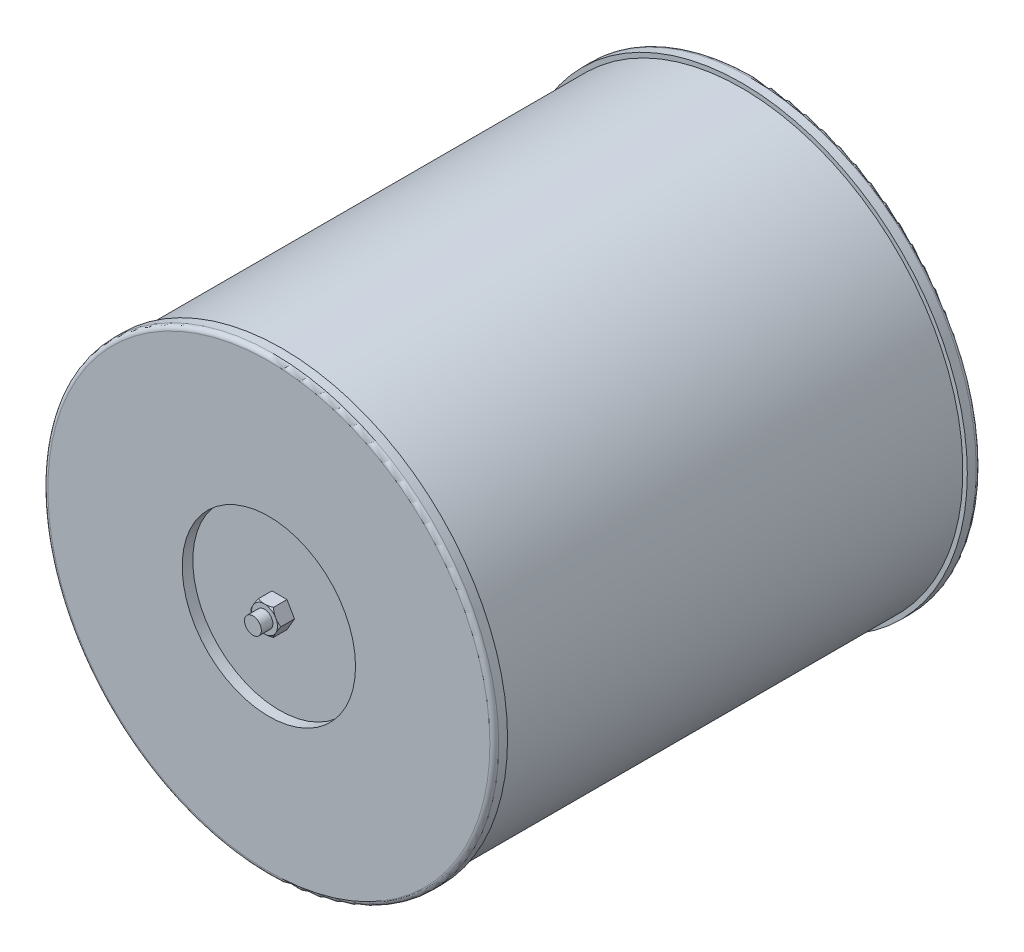
SolidWorks part; units mm, degrees
ref_plane "Alzado" through (0, 0, 0) normal (0, 0, 1) x (1, 0, 0)
ref_plane "Planta" through (0, 0, 0) normal (0, 1, 0) x (1, 0, 0)
ref_plane "Vista lateral" through (0, 0, 0) normal (1, 0, 0) x (0, 0, -1)
sketch "Croquis1" plane through (0, 0, 0) normal (0, 0, 1) x (1, 0, 0)
  circle A0 centre (0, 0) radius 165
  dimension "D1" = 330
extrude "Saliente-Extruir1" add sketch "Croquis1" along normal blind 4
sketch "Croquis2" plane through (0, 0, 4) normal (0, 0, 1) x (1, 0, 0)
  circle A0 centre (0, 0) radius 122
  dimension "D1" = 244
extrude "Saliente-Extruir2" add sketch "Croquis2" along normal blind 50
sketch "Croquis3" plane through (0, 0, 54) normal (0, 0, 1) x (1, 0, 0)
  circle A0 centre (0, 0) radius 250
  dimension "D1" = 500
extrude "Saliente-Extruir3" add sketch "Croquis3" along normal blind 550
sketch "Croquis4" plane through (0, 0, 54) normal (0, 0, -1) x (-1, 0, 0)
  circle A0 centre (0, 0) radius 255
  dimension "D1" = 510
extrude "Saliente-Extruir4" add sketch "Croquis4" against normal blind 15
sketch "Croquis5" plane through (0, 0, 604) normal (0, 0, 1) x (1, 0, 0)
  circle A0 centre (0, 0) radius 255
extrude "Saliente-Extruir5" add sketch "Croquis5" against normal blind 15
fillet "Redondeo1" radius 5 2 edges at (-255, 0, 54) (255, 0, 604)
sketch "Croquis6" plane through (0, 0, 604) normal (0, 0, 1) x (1, 0, 0)
  circle A0 centre (0, 0) radius 98.0247
extrude "Cortar-Extruir1" cut sketch "Croquis6" against normal blind 12
sketch "Croquis7" plane through (0, 0, 592) normal (0, 0, 1) x (1, 0, 0)
  circle A0 centre (0, 0) radius 9.525
  dimension "D1" = 19.05
extrude "Saliente-Extruir6" add sketch "Croquis7" along normal blind 30
sketch "Croquis8" plane through (0, 0, 592) normal (0, 0, 1) x (1, 0, 0)
  line L1 (17, 0) -> (8.5, 14.7224)
  line L2 (8.5, 14.7224) -> (-8.5, 14.7224)
  line L3 (-8.5, 14.7224) -> (-17, 0)
  line L4 (-17, 0) -> (-8.5, -14.7224)
  line L5 (-8.5, -14.7224) -> (8.5, -14.7224)
  line L6 (8.5, -14.7224) -> (17, 0)
  circle A0 centre (0, 0) radius 14.7224 construction
  dimension "D1" = 34
extrude "Saliente-Extruir7" add sketch "Croquis8" along normal blind 17
sketch "Croquis9" plane through (0, 0, 609) normal (0, 0, 1) x (1, 0, 0)
  circle A0 centre (0, 0) radius 14.7224
  circle A1 centre (0, 0) radius 43.1338
extrude "Cortar-Extruir2" cut sketch "Croquis9" against normal blind 10 draft 55
